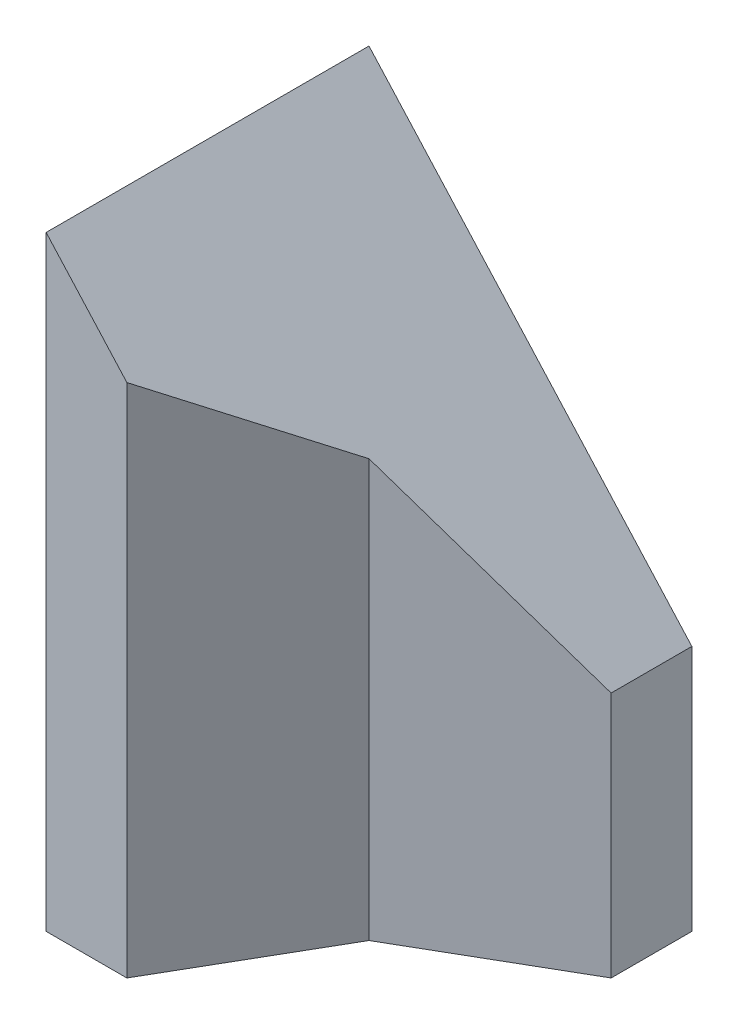
SolidWorks part; units mm, degrees
ref_plane "Front Plane" through (0, 0, 0) normal (0, 0, 1) x (1, 0, 0)
ref_plane "Top Plane" through (0, 0, 0) normal (0, 1, 0) x (1, 0, 0)
ref_plane "Right Plane" through (0, 0, 0) normal (1, 0, 0) x (0, 0, -1)
sketch "Sketch1" plane through (0, 0, 0) normal (0, 1, 0) x (1, 0, 0)
  line L0 (50.8, 0) -> (0, 0)
  line L1 (0, 0) -> (0, -50.8)
  line L2 (0, -50.8) -> (12.7, -50.8)
  line L3 (26.6456, -26.6456) -> (12.7, -50.8)
  line L4 (26.6456, -26.6456) -> (50.8, -12.7)
  line L5 (50.8, -12.7) -> (50.8, 0)
  line L6 (12.7, -50.8) -> (50.8, -50.8) construction
  line L7 (50.8, -50.8) -> (50.8, -12.7) construction
  dimension "D1" = 50.8
  dimension "D2" = 60
  dimension "D3" = 60
  dimension "D4" = 38.1
  dimension "D5" = 38.1
extrude "Boss-Extrude1" add sketch "Sketch1" along normal blind 95.25
sketch "Sketch2" plane through (0, 0, 0) normal (0, 0, 1) x (1, 0, 0)
  line L0 (0, 95.25) -> (50.8, 38.8309)
  line L1 (50.8, 95.25) -> (50.8, 0) construction
  line L2 (0, 95.25) -> (0, 0) construction
  dimension "D1" = 42
extrude "Cut-Extrude1" cut sketch "Sketch2" against normal through all and the other way through all
